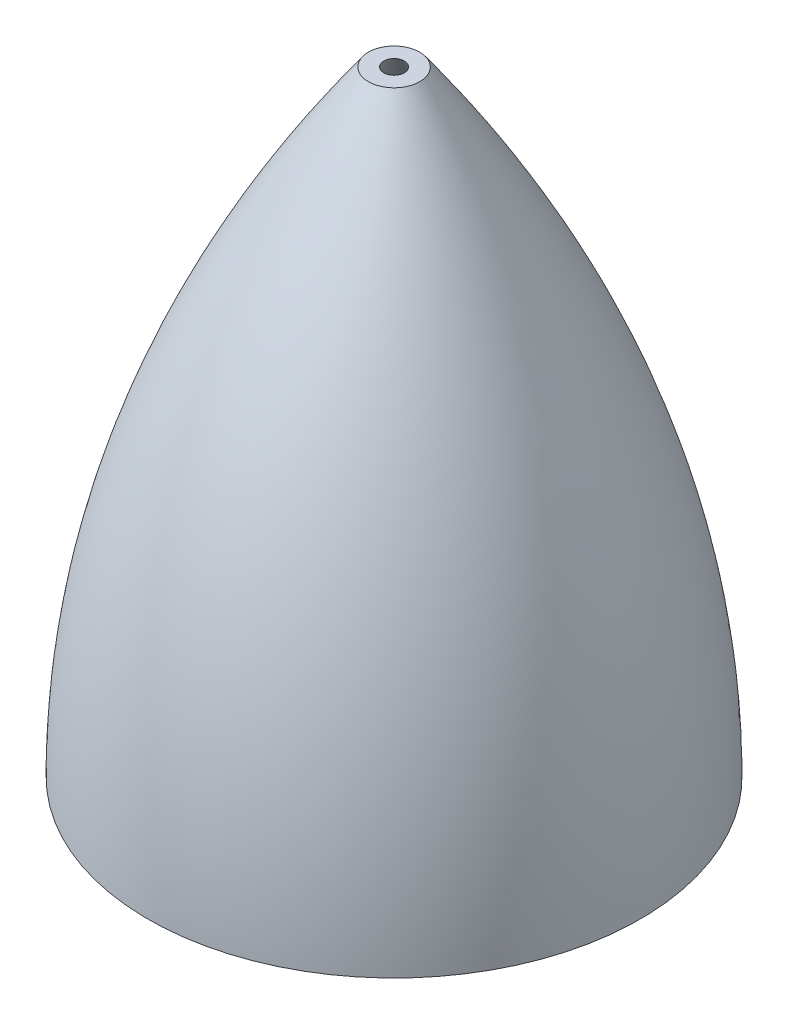
SolidWorks part; units mm, degrees
ref_plane "Front Plane" through (0, 0, 0) normal (0, 0, 1) x (1, 0, 0)
ref_plane "Top Plane" through (0, 0, 0) normal (0, 1, 0) x (1, 0, 0)
ref_plane "Right Plane" through (0, 0, 0) normal (1, 0, 0) x (0, 0, -1)
sketch "Sketch12" plane through (0, 0, 0) normal (0, 0, 1) x (1, 0, 0)
  line L5 (0, 120) -> (0, 0) construction
  line L6 (5, 120) -> (2, 120)
  line L7 (48, 0) -> (45, 0)
  spline S0 degree 2 poles (45, 0) (45, 60) (2, 120) knots 0 0 0 1 1 1 construction
  spline S1 degree 2 poles (45, 0) (45, 60) (2, 120) knots 0 0 0 1 1 1
  spline S2 degree 2 poles (48, 0) (48, 60) (5, 120) knots 0 0 0 1 1 1 construction
  spline S3 degree 2 poles (48, 0) (48, 60) (5, 120) knots 0 0 0 1 1 1
  dimension "D1" = 2
  dimension "D2" = 45
revolve "Revolve9" add sketch "Sketch12" angle 360 about L5
